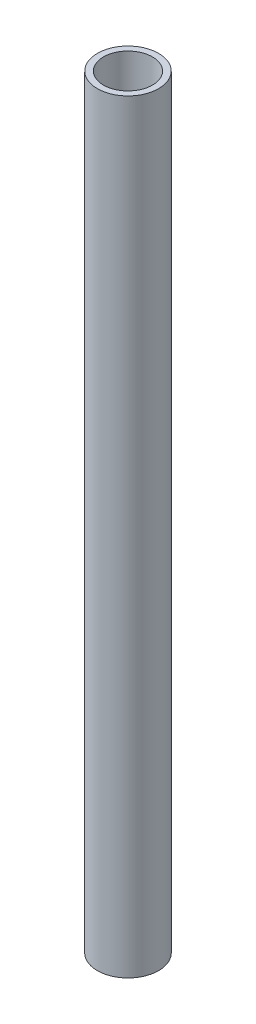
SolidWorks part; units mm, degrees
ref_plane "Front Plane" through (0, 0, 0) normal (0, 0, 1) x (1, 0, 0)
ref_plane "Top Plane" through (0, 0, 0) normal (0, 1, 0) x (1, 0, 0)
ref_plane "Right Plane" through (0, 0, 0) normal (1, 0, 0) x (0, 0, -1)
sketch "Sketch1" plane through (0, 0, 0) normal (0, 1, 0) x (1, 0, 0)
  circle A0 centre (0, 0) radius 1.25
  circle A1 centre (0, 0) radius 1
extrude "Boss-Extrude1" add sketch "Sketch1" along normal blind 31.2
